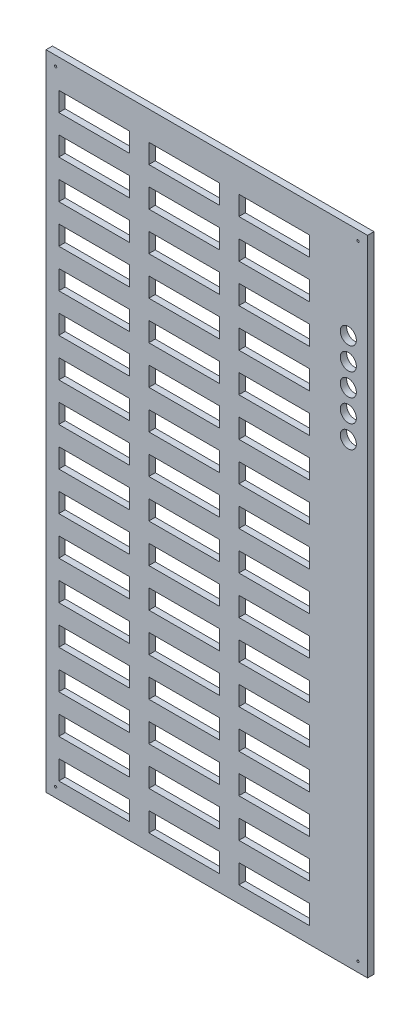
SolidWorks part; units mm, degrees
ref_plane "Plan de face" through (0, 0, 0) normal (0, 0, 1) x (1, 0, 0)
ref_plane "Plan de dessus" through (0, 0, 0) normal (0, 1, 0) x (1, 0, 0)
ref_plane "Plan de droite" through (0, 0, 0) normal (1, 0, 0) x (0, 0, -1)
sketch "Esquisse1" plane through (0, 0, 0) normal (0, 0, 1) x (1, 0, 0)
  line L0 (0, 0) -> (0, -50000) construction
  line L1 (-250, 500) -> (250, 500)
  line L2 (-250, 500) -> (-250, -500)
  line L3 (-250, -500) -> (250, -500)
  line L4 (250, 500) -> (250, -500)
  line L5 (-250, 500) -> (250, -500) construction
  line L6 (-250, -500) -> (250, 500) construction
  line L7 (0, 0) -> (50000, 0) construction
  line L8 (235, 485) -> (235, 500) construction
  line L9 (235, 485) -> (250, 485) construction
  line L10 (220, 350) -> (220, 315) construction
  line L11 (220, 315) -> (220, 280) construction
  line L12 (220, 280) -> (220, 245) construction
  line L13 (220, 245) -> (220, 210) construction
  line L14 (220, 210) -> (220, -500) construction
  line L15 (220, 350) -> (220, 500) construction
  circle A0 centre (235, 485) radius 1.75
  circle A2 centre (235, -485) radius 1.75
  circle A3 centre (220, 350) radius 12.5
  circle A4 centre (220, 315) radius 12.5
  circle A5 centre (220, 245) radius 12.5
  circle A6 centre (220, 280) radius 12.5
  circle A7 centre (220, 210) radius 12.5
  circle A8 centre (-235, -485) radius 1.75
  circle A9 centre (-235, 485) radius 1.75
  point P0 (0, 0)
  dimension "D3" = 3.5
  dimension "D5" = 25
  dimension "D1" = 1000
  dimension "D2" = 500
  dimension "D4" = 15
  dimension "D6" = 35
  dimension "D7" = 30
  dimension "D10" = 150
extrude "Boss.-Extru.1" add sketch "Esquisse1" along normal blind 10
sketch "Esquisse3" plane through (0, 0, 10) normal (0, 0, 1) x (1, 0, 0)
  line L0 (-250, 440.3401) -> (250, 440.3401) construction
  line L1 (-230.1295, 455.3401) -> (-120.1295, 455.3401)
  line L2 (-230.1295, 455.3401) -> (-230.1295, 425.3401)
  line L3 (-230.1295, 425.3401) -> (-120.1295, 425.3401)
  line L4 (-120.1295, 455.3401) -> (-120.1295, 425.3401)
  line L5 (-230.1295, 455.3401) -> (-120.1295, 425.3401) construction
  line L6 (-230.1295, 425.3401) -> (-120.1295, 455.3401) construction
  line L7 (-250, 500) -> (-250, -500) construction
  line L8 (250, -500) -> (250, 500) construction
  line L9 (-90.1295, 455.3401) -> (19.8705, 455.3401)
  line L10 (-90.1295, 455.3401) -> (-90.1295, 425.3401)
  line L11 (-90.1295, 425.3401) -> (19.8705, 425.3401)
  line L12 (19.8705, 455.3401) -> (19.8705, 425.3401)
  line L13 (49.8705, 455.3401) -> (159.8705, 455.3401)
  line L14 (49.8705, 455.3401) -> (49.8705, 425.3401)
  line L15 (49.8705, 425.3401) -> (159.8705, 425.3401)
  line L16 (159.8705, 455.3401) -> (159.8705, 425.3401)
  line L17 (-90.1295, 395.3401) -> (19.8705, 395.3401)
  line L18 (-90.1295, 395.3401) -> (-90.1295, 365.3401)
  line L19 (-90.1295, 365.3401) -> (19.8705, 365.3401)
  line L20 (19.8705, 395.3401) -> (19.8705, 365.3401)
  line L21 (49.8705, 395.3401) -> (159.8705, 395.3401)
  line L22 (49.8705, 395.3401) -> (49.8705, 365.3401)
  line L23 (49.8705, 365.3401) -> (159.8705, 365.3401)
  line L24 (159.8705, 395.3401) -> (159.8705, 365.3401)
  line L25 (-90.1295, 335.3401) -> (19.8705, 335.3401)
  line L26 (-90.1295, 335.3401) -> (-90.1295, 305.3401)
  line L27 (-90.1295, 305.3401) -> (19.8705, 305.3401)
  line L28 (19.8705, 335.3401) -> (19.8705, 305.3401)
  line L29 (49.8705, 335.3401) -> (159.8705, 335.3401)
  line L30 (49.8705, 335.3401) -> (49.8705, 305.3401)
  line L31 (49.8705, 305.3401) -> (159.8705, 305.3401)
  line L32 (159.8705, 335.3401) -> (159.8705, 305.3401)
  line L33 (-90.1295, 275.3401) -> (19.8705, 275.3401)
  line L34 (-90.1295, 275.3401) -> (-90.1295, 245.3401)
  line L35 (-90.1295, 245.3401) -> (19.8705, 245.3401)
  line L36 (19.8705, 275.3401) -> (19.8705, 245.3401)
  line L37 (49.8705, 275.3401) -> (159.8705, 275.3401)
  line L38 (49.8705, 275.3401) -> (49.8705, 245.3401)
  line L39 (49.8705, 245.3401) -> (159.8705, 245.3401)
  line L40 (159.8705, 275.3401) -> (159.8705, 245.3401)
  line L41 (-90.1295, 215.3401) -> (19.8705, 215.3401)
  line L42 (-90.1295, 215.3401) -> (-90.1295, 185.3401)
  line L43 (-90.1295, 185.3401) -> (19.8705, 185.3401)
  line L44 (19.8705, 215.3401) -> (19.8705, 185.3401)
  line L45 (49.8705, 215.3401) -> (159.8705, 215.3401)
  line L46 (49.8705, 215.3401) -> (49.8705, 185.3401)
  line L47 (49.8705, 185.3401) -> (159.8705, 185.3401)
  line L48 (159.8705, 215.3401) -> (159.8705, 185.3401)
  line L49 (-90.1295, 155.3401) -> (19.8705, 155.3401)
  line L50 (-90.1295, 155.3401) -> (-90.1295, 125.3401)
  line L51 (-90.1295, 125.3401) -> (19.8705, 125.3401)
  line L52 (19.8705, 155.3401) -> (19.8705, 125.3401)
  line L53 (49.8705, 155.3401) -> (159.8705, 155.3401)
  line L54 (49.8705, 155.3401) -> (49.8705, 125.3401)
  line L55 (49.8705, 125.3401) -> (159.8705, 125.3401)
  line L56 (159.8705, 155.3401) -> (159.8705, 125.3401)
  line L57 (-90.1295, 95.3401) -> (19.8705, 95.3401)
  line L58 (-90.1295, 95.3401) -> (-90.1295, 65.3401)
  line L59 (-90.1295, 65.3401) -> (19.8705, 65.3401)
  line L60 (19.8705, 95.3401) -> (19.8705, 65.3401)
  line L61 (49.8705, 95.3401) -> (159.8705, 95.3401)
  line L62 (49.8705, 95.3401) -> (49.8705, 65.3401)
  line L63 (49.8705, 65.3401) -> (159.8705, 65.3401)
  line L64 (159.8705, 95.3401) -> (159.8705, 65.3401)
  line L65 (-90.1295, 35.3401) -> (19.8705, 35.3401)
  line L66 (-90.1295, 35.3401) -> (-90.1295, 5.3401)
  line L67 (-90.1295, 5.3401) -> (19.8705, 5.3401)
  line L68 (19.8705, 35.3401) -> (19.8705, 5.3401)
  line L69 (49.8705, 35.3401) -> (159.8705, 35.3401)
  line L70 (49.8705, 35.3401) -> (49.8705, 5.3401)
  line L71 (49.8705, 5.3401) -> (159.8705, 5.3401)
  line L72 (159.8705, 35.3401) -> (159.8705, 5.3401)
  line L73 (-90.1295, -24.6599) -> (19.8705, -24.6599)
  line L74 (-90.1295, -24.6599) -> (-90.1295, -54.6599)
  line L75 (-90.1295, -54.6599) -> (19.8705, -54.6599)
  line L76 (19.8705, -24.6599) -> (19.8705, -54.6599)
  line L77 (49.8705, -24.6599) -> (159.8705, -24.6599)
  line L78 (49.8705, -24.6599) -> (49.8705, -54.6599)
  line L79 (49.8705, -54.6599) -> (159.8705, -54.6599)
  line L80 (159.8705, -24.6599) -> (159.8705, -54.6599)
  line L81 (-90.1295, -84.6599) -> (19.8705, -84.6599)
  line L82 (-90.1295, -84.6599) -> (-90.1295, -114.6599)
  line L83 (-90.1295, -114.6599) -> (19.8705, -114.6599)
  line L84 (19.8705, -84.6599) -> (19.8705, -114.6599)
  line L85 (49.8705, -84.6599) -> (159.8705, -84.6599)
  line L86 (49.8705, -84.6599) -> (49.8705, -114.6599)
  line L87 (49.8705, -114.6599) -> (159.8705, -114.6599)
  line L88 (159.8705, -84.6599) -> (159.8705, -114.6599)
  line L89 (-90.1295, -144.6599) -> (19.8705, -144.6599)
  line L90 (-90.1295, -144.6599) -> (-90.1295, -174.6599)
  line L91 (-90.1295, -174.6599) -> (19.8705, -174.6599)
  line L92 (19.8705, -144.6599) -> (19.8705, -174.6599)
  line L93 (49.8705, -144.6599) -> (159.8705, -144.6599)
  line L94 (49.8705, -144.6599) -> (49.8705, -174.6599)
  line L95 (49.8705, -174.6599) -> (159.8705, -174.6599)
  line L96 (159.8705, -144.6599) -> (159.8705, -174.6599)
  line L97 (-90.1295, -204.6599) -> (19.8705, -204.6599)
  line L98 (-90.1295, -204.6599) -> (-90.1295, -234.6599)
  line L99 (-90.1295, -234.6599) -> (19.8705, -234.6599)
  line L100 (19.8705, -204.6599) -> (19.8705, -234.6599)
  line L101 (49.8705, -204.6599) -> (159.8705, -204.6599)
  line L102 (49.8705, -204.6599) -> (49.8705, -234.6599)
  line L103 (49.8705, -234.6599) -> (159.8705, -234.6599)
  line L104 (159.8705, -204.6599) -> (159.8705, -234.6599)
  line L105 (-90.1295, -264.6599) -> (19.8705, -264.6599)
  line L106 (-90.1295, -264.6599) -> (-90.1295, -294.6599)
  line L107 (-90.1295, -294.6599) -> (19.8705, -294.6599)
  line L108 (19.8705, -264.6599) -> (19.8705, -294.6599)
  line L109 (49.8705, -264.6599) -> (159.8705, -264.6599)
  line L110 (49.8705, -264.6599) -> (49.8705, -294.6599)
  line L111 (49.8705, -294.6599) -> (159.8705, -294.6599)
  line L112 (159.8705, -264.6599) -> (159.8705, -294.6599)
  line L113 (-90.1295, -324.6599) -> (19.8705, -324.6599)
  line L114 (-90.1295, -324.6599) -> (-90.1295, -354.6599)
  line L115 (-90.1295, -354.6599) -> (19.8705, -354.6599)
  line L116 (19.8705, -324.6599) -> (19.8705, -354.6599)
  line L117 (49.8705, -324.6599) -> (159.8705, -324.6599)
  line L118 (49.8705, -324.6599) -> (49.8705, -354.6599)
  line L119 (49.8705, -354.6599) -> (159.8705, -354.6599)
  line L120 (159.8705, -324.6599) -> (159.8705, -354.6599)
  line L121 (-90.1295, -384.6599) -> (19.8705, -384.6599)
  line L122 (-90.1295, -384.6599) -> (-90.1295, -414.6599)
  line L123 (-90.1295, -414.6599) -> (19.8705, -414.6599)
  line L124 (19.8705, -384.6599) -> (19.8705, -414.6599)
  line L125 (49.8705, -384.6599) -> (159.8705, -384.6599)
  line L126 (49.8705, -384.6599) -> (49.8705, -414.6599)
  line L127 (49.8705, -414.6599) -> (159.8705, -414.6599)
  line L128 (159.8705, -384.6599) -> (159.8705, -414.6599)
  line L129 (-90.1295, -444.6599) -> (19.8705, -444.6599)
  line L130 (-90.1295, -444.6599) -> (-90.1295, -474.6599)
  line L131 (-90.1295, -474.6599) -> (19.8705, -474.6599)
  line L132 (19.8705, -444.6599) -> (19.8705, -474.6599)
  line L133 (49.8705, -444.6599) -> (159.8705, -444.6599)
  line L134 (49.8705, -444.6599) -> (49.8705, -474.6599)
  line L135 (49.8705, -474.6599) -> (159.8705, -474.6599)
  line L136 (159.8705, -444.6599) -> (159.8705, -474.6599)
  line L137 (-230.1295, 395.3401) -> (-120.1295, 395.3401)
  line L138 (-230.1295, 395.3401) -> (-230.1295, 365.3401)
  line L139 (-230.1295, 365.3401) -> (-120.1295, 365.3401)
  line L140 (-120.1295, 395.3401) -> (-120.1295, 365.3401)
  line L141 (-230.1295, 335.3401) -> (-120.1295, 335.3401)
  line L142 (-230.1295, 335.3401) -> (-230.1295, 305.3401)
  line L143 (-230.1295, 305.3401) -> (-120.1295, 305.3401)
  line L144 (-120.1295, 335.3401) -> (-120.1295, 305.3401)
  line L145 (-230.1295, 275.3401) -> (-120.1295, 275.3401)
  line L146 (-230.1295, 275.3401) -> (-230.1295, 245.3401)
  line L147 (-230.1295, 245.3401) -> (-120.1295, 245.3401)
  line L148 (-120.1295, 275.3401) -> (-120.1295, 245.3401)
  line L149 (-230.1295, 215.3401) -> (-120.1295, 215.3401)
  line L150 (-230.1295, 215.3401) -> (-230.1295, 185.3401)
  line L151 (-230.1295, 185.3401) -> (-120.1295, 185.3401)
  line L152 (-120.1295, 215.3401) -> (-120.1295, 185.3401)
  line L153 (-230.1295, 155.3401) -> (-120.1295, 155.3401)
  line L154 (-230.1295, 155.3401) -> (-230.1295, 125.3401)
  line L155 (-230.1295, 125.3401) -> (-120.1295, 125.3401)
  line L156 (-120.1295, 155.3401) -> (-120.1295, 125.3401)
  line L157 (-230.1295, 95.3401) -> (-120.1295, 95.3401)
  line L158 (-230.1295, 95.3401) -> (-230.1295, 65.3401)
  line L159 (-230.1295, 65.3401) -> (-120.1295, 65.3401)
  line L160 (-120.1295, 95.3401) -> (-120.1295, 65.3401)
  line L161 (-230.1295, 35.3401) -> (-120.1295, 35.3401)
  line L162 (-230.1295, 35.3401) -> (-230.1295, 5.3401)
  line L163 (-230.1295, 5.3401) -> (-120.1295, 5.3401)
  line L164 (-120.1295, 35.3401) -> (-120.1295, 5.3401)
  line L165 (-230.1295, -24.6599) -> (-120.1295, -24.6599)
  line L166 (-230.1295, -24.6599) -> (-230.1295, -54.6599)
  line L167 (-230.1295, -54.6599) -> (-120.1295, -54.6599)
  line L168 (-120.1295, -24.6599) -> (-120.1295, -54.6599)
  line L169 (-230.1295, -84.6599) -> (-120.1295, -84.6599)
  line L170 (-230.1295, -84.6599) -> (-230.1295, -114.6599)
  line L171 (-230.1295, -114.6599) -> (-120.1295, -114.6599)
  line L172 (-120.1295, -84.6599) -> (-120.1295, -114.6599)
  line L173 (-230.1295, -144.6599) -> (-120.1295, -144.6599)
  line L174 (-230.1295, -144.6599) -> (-230.1295, -174.6599)
  line L175 (-230.1295, -174.6599) -> (-120.1295, -174.6599)
  line L176 (-120.1295, -144.6599) -> (-120.1295, -174.6599)
  line L177 (-230.1295, -204.6599) -> (-120.1295, -204.6599)
  line L178 (-230.1295, -204.6599) -> (-230.1295, -234.6599)
  line L179 (-230.1295, -234.6599) -> (-120.1295, -234.6599)
  line L180 (-120.1295, -204.6599) -> (-120.1295, -234.6599)
  line L181 (-230.1295, -264.6599) -> (-120.1295, -264.6599)
  line L182 (-230.1295, -264.6599) -> (-230.1295, -294.6599)
  line L183 (-230.1295, -294.6599) -> (-120.1295, -294.6599)
  line L184 (-120.1295, -264.6599) -> (-120.1295, -294.6599)
  line L185 (-230.1295, -324.6599) -> (-120.1295, -324.6599)
  line L186 (-230.1295, -324.6599) -> (-230.1295, -354.6599)
  line L187 (-230.1295, -354.6599) -> (-120.1295, -354.6599)
  line L188 (-120.1295, -324.6599) -> (-120.1295, -354.6599)
  line L189 (-230.1295, -384.6599) -> (-120.1295, -384.6599)
  line L190 (-230.1295, -384.6599) -> (-230.1295, -414.6599)
  line L191 (-230.1295, -414.6599) -> (-120.1295, -414.6599)
  line L192 (-120.1295, -384.6599) -> (-120.1295, -414.6599)
  line L193 (-230.1295, -444.6599) -> (-120.1295, -444.6599)
  line L194 (-230.1295, -444.6599) -> (-230.1295, -474.6599)
  line L195 (-230.1295, -474.6599) -> (-120.1295, -474.6599)
  line L196 (-120.1295, -444.6599) -> (-120.1295, -474.6599)
  line L197 (-250, 0) -> (49750, 0) construction
  line L198 (0, 0) -> (0, -50000) construction
  point P0 (-175.1295, 440.3401)
  point P13 (-250, 0)
  dimension "D1" = 110
  dimension "D2" = 30
  dimension "D3" = 3
  dimension "D4" = 16
extrude "Enlèv. mat.-Extru.2" cut sketch "Esquisse3" against normal up to surface (10 mm away) up to face at (0, 0, 0)
